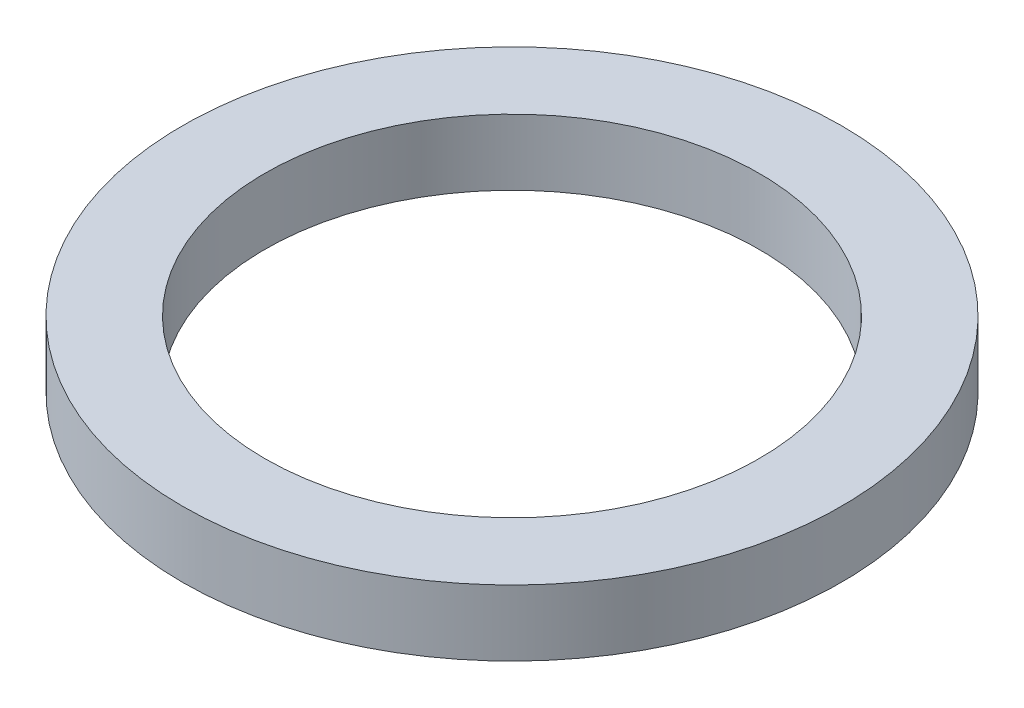
SolidWorks part; units mm, degrees
ref_plane "Front Plane" through (0, 0, 0) normal (0, 0, 1) x (1, 0, 0)
ref_plane "Top Plane" through (0, 0, 0) normal (0, 1, 0) x (1, 0, 0)
ref_plane "Right Plane" through (0, 0, 0) normal (1, 0, 0) x (0, 0, -1)
sketch "Sketch1" plane through (0, 0, 0) normal (0, 1, 0) x (1, 0, 0)
  circle A0 centre (0, 0) radius 10
  dimension "D1" = 20
extrude "Boss-Extrude1" add sketch "Sketch1" along normal blind 2
sketch "Sketch2" plane through (0, 2, 0) normal (0, 1, 0) x (1, 0, 0)
  circle A0 centre (0, 0) radius 7.5
  dimension "D1" = 15
extrude "Cut-Extrude1" cut sketch "Sketch2" against normal up to next contours A0
